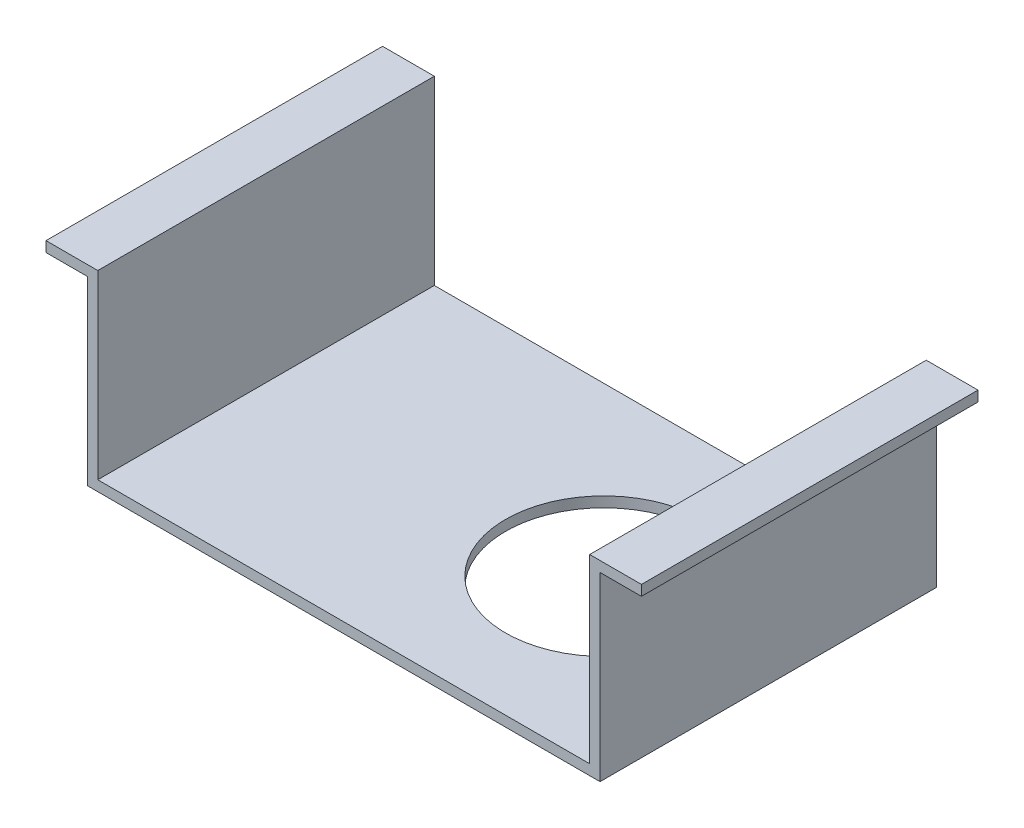
SolidWorks part; units mm, degrees
material "ABS"
ref_plane "Front Plane" through (0, 0, 0) normal (0, 0, 1) x (1, 0, 0)
ref_plane "Top Plane" through (0, 0, 0) normal (0, 1, 0) x (1, 0, 0)
ref_plane "Right Plane" through (0, 0, 0) normal (1, 0, 0) x (0, 0, -1)
sketch "Sketch1" plane through (0, 0, 0) normal (0, 0, 1) x (1, 0, 0)
  line L0 (-15.2278, 6.0123) -> (-5.2278, 6.0123)
  line L1 (-5.2278, 6.0123) -> (-5.2278, -28.9877)
  line L2 (-5.2278, -28.9877) -> (89.7722, -28.9877)
  line L3 (89.7722, -28.9877) -> (89.7722, 6.0123)
  line L4 (89.7722, 6.0123) -> (99.7722, 6.0123)
  line L5 (99.7722, 6.0123) -> (99.7722, 4.0123)
  line L6 (99.7722, 4.0123) -> (91.7722, 4.0123)
  line L7 (91.7722, 4.0123) -> (91.7722, -30.9877)
  line L8 (91.7722, -30.9877) -> (-7.2278, -30.9877)
  line L9 (-7.2278, -30.9877) -> (-7.2278, 4.0123)
  line L10 (-7.2278, 4.0123) -> (-15.2278, 4.0123)
  line L11 (-15.2278, 4.0123) -> (-15.2278, 6.0123)
  dimension "D1" = 2
  dimension "D2" = 2
  dimension "D3" = 2
  dimension "D4" = 2
  dimension "D5" = 2
  dimension "D6" = 95
  dimension "D7" = 8
  dimension "D8" = 8
  dimension "D9" = 35
  dimension "D10" = 35
extrude "Boss-Extrude1" add sketch "Sketch1" along normal blind 65
sketch "Sketch2" plane through (0, -30.9877, 0) normal (0, -1, 0) x (1, 0, 0)
  line L0 (91.7722, 65) -> (91.7722, 0) construction
  circle A0 centre (59.7722, 32.2531) radius 19
  point P2 (91.7722, 32.5)
  dimension "D1" = 32
extrude "Cut-Extrude1" cut sketch "Sketch2" against normal through all
